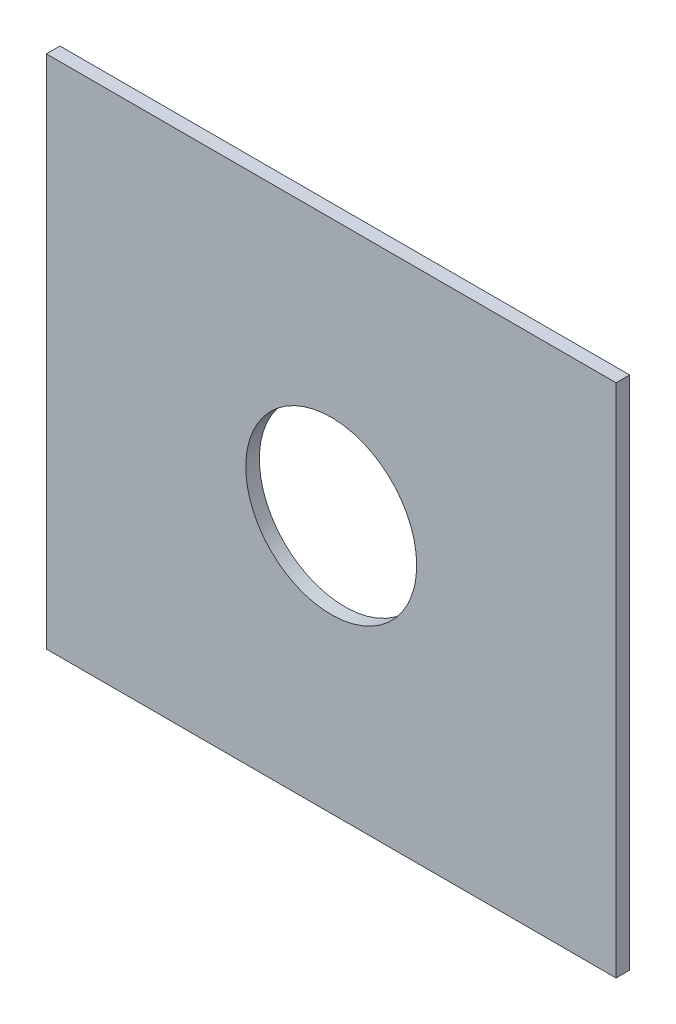
SolidWorks part; units mm, degrees
ref_plane "Front Plane" through (0, 0, 0) normal (0, 0, 1) x (1, 0, 0)
ref_plane "Top Plane" through (0, 0, 0) normal (0, 1, 0) x (1, 0, 0)
ref_plane "Right Plane" through (0, 0, 0) normal (1, 0, 0) x (0, 0, -1)
sketch "Local second layer and bore profile" plane through (0, 0, 0) normal (0, 0, 1) x (1, 0, 0)
  line L0 (-21, 9.5) -> (21, 9.5)
  line L1 (21, 9.5) -> (21, 47.5)
  line L2 (21, 47.5) -> (-21, 47.5)
  line L3 (-21, 47.5) -> (-21, 9.5)
  circle A0 centre (0, 28.5) radius 6.3
extrude "Local second layer and bore" add sketch "Local second layer and bore profile" along normal blind 1
